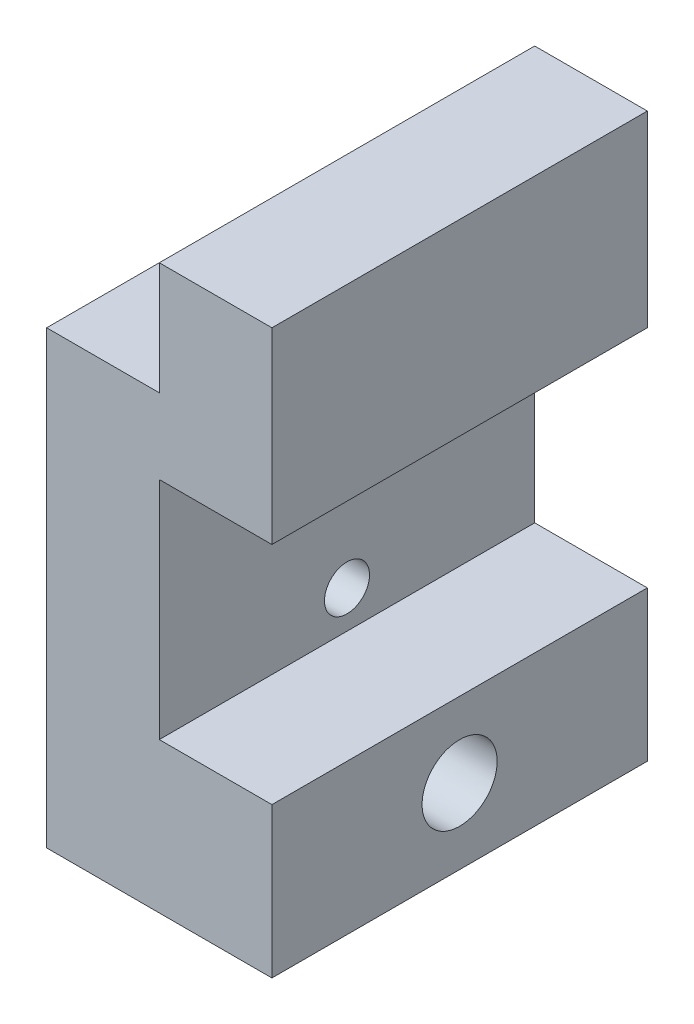
SolidWorks part; units mm, degrees
ref_plane "Front Plane" through (0, 0, 0) normal (0, 0, 1) x (1, 0, 0)
ref_plane "Top Plane" through (0, 0, 0) normal (0, 1, 0) x (1, 0, 0)
ref_plane "Right Plane" through (0, 0, 0) normal (1, 0, 0) x (0, 0, -1)
sketch "Sketch1" plane through (0, 0, 0) normal (0, 0, 1) x (1, 0, 0)
  line L0 (0, 0) -> (68952.629, 0) construction
  line L1 (104.6471, 0) -> (104.6471, 68952.629) construction
  line L2 (104.7021, 60) -> (30, 60) construction
  line L3 (0, 51.7317) -> (0, -68900.8974) construction
  line L4 (30, 0) -> (0, 0)
  line L5 (0, 0) -> (0, 60)
  line L6 (0, 60) -> (15, 60)
  line L7 (30, 60) -> (30, 50)
  line L8 (30, 50) -> (15, 50)
  line L9 (15, 50) -> (15, 20)
  line L10 (15, 20) -> (30, 20)
  line L11 (30, 20) -> (30, 0)
  line L12 (30, 60) -> (30, 75)
  line L13 (30, 75) -> (15, 75)
  line L14 (15, 75) -> (15, 60)
  line L15 (15, 60) -> (-68847.9269, 60) construction
  dimension "D1" = 30
  dimension "D2" = 15
  dimension "D3" = 10
  dimension "D4" = 20
  dimension "D5" = 15
  dimension "D6" = 15
  dimension "D7" = 30
extrude "Boss-Extrude1" add sketch "Sketch1" against normal blind 50
sketch "Sketch2" plane through (30, 0, 0) normal (1, 0, 0) x (0, 0, -1)
  line L0 (25, 0) -> (25, 20) construction
  line L1 (50, 0) -> (0, 0) construction
  line L2 (50, 20) -> (0, 20) construction
  circle A0 centre (25, 10) radius 5
extrude "Cut-Extrude1" cut sketch "Sketch2" against normal blind 50
sketch "Sketch3" plane through (0, 0, 0) normal (-1, 0, 0) x (0, 0, 1)
  line L0 (-25, 0) -> (-25, 60) construction
  line L1 (-50, 0) -> (0, 0) construction
  line L2 (-50, 60) -> (0, 60) construction
  line L4 (-50, 50) -> (0, 50) construction
  line L5 (0, 60) -> (0, 0) construction
  line L6 (102.0729, 50) -> (-147.9271, 50) construction
  circle A0 centre (-25, 25) radius 3
  dimension "D1" = 25
extrude "Cut-Extrude2" cut sketch "Sketch3" against normal blind 101
